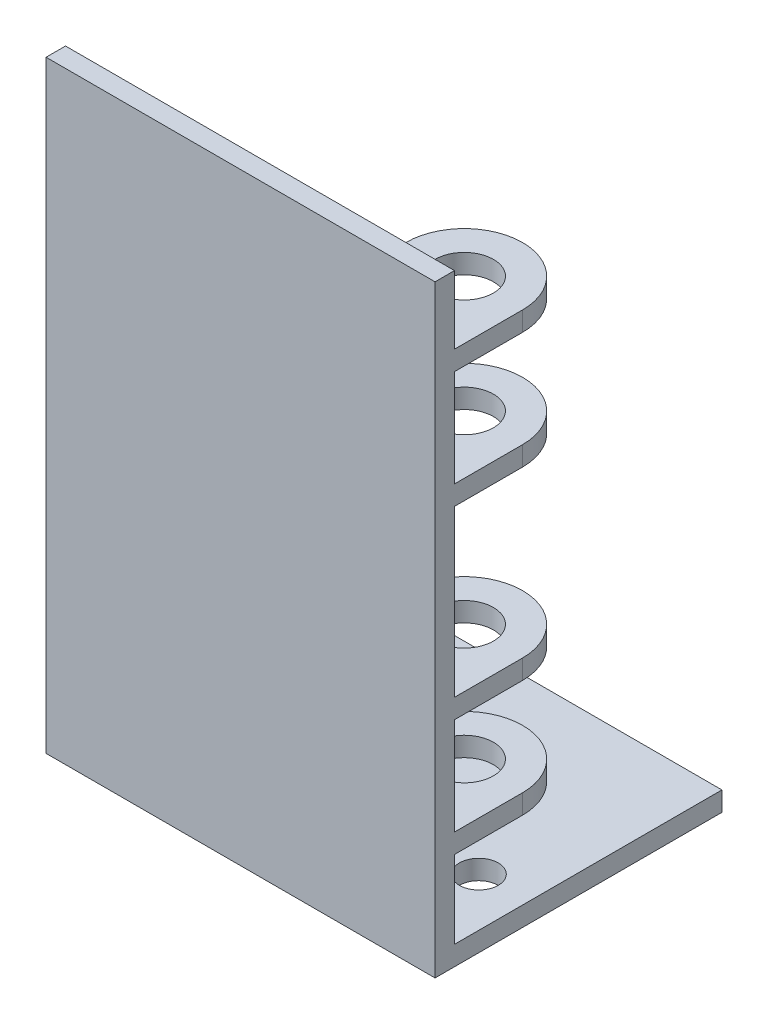
SolidWorks part; units mm, degrees
material "AISI 1045 Acero estirado en frío"
ref_plane "Front" through (0, 0, 0) normal (0, 0, 1) x (1, 0, 0)
ref_plane "Top" through (0, 0, 0) normal (0, 1, 0) x (1, 0, 0)
ref_plane "Right" through (0, 0, 0) normal (1, 0, 0) x (0, 0, -1)
sketch "Croquis2" plane through (0, 0, 0) normal (0, 1, 0) x (1, 0, 0)
  line L1 (20, 55) -> (20, 0) construction
  line L2 (0, 0) -> (40, 0)
  line L3 (0, 0) -> (0, 55)
  line L4 (0, 55) -> (40, 55)
  line L5 (40, 0) -> (40, 55)
  circle A0 centre (5, 47.5) radius 2
  circle A1 centre (35, 47.5) radius 2
  circle A2 centre (35, 7.5) radius 2
  circle A3 centre (5, 7.5) radius 2
  dimension "D2" = 30
  dimension "D3" = 4
  dimension "D4" = 7.5
  dimension "D5" = 5
  dimension "D6" = 7.5
  dimension "D7" = 40
  dimension "D1" = 5
  dimension "5.5" = 55
extrude "Saliente-Extruir1" add sketch "Croquis2" along normal blind 2
sketch "Croquis3" plane through (0, 0, 0) normal (0, 1, 0) x (1, 0, 0)
  line L0 (40, 0) -> (40, 55) construction
  line L1 (0, 0) -> (40, 0)
  line L2 (0, 0) -> (0, -2)
  line L3 (0, -2) -> (40, -2)
  line L4 (40, 0) -> (40, -2)
  dimension "D1" = 2
extrude "Saliente-Extruir2" add sketch "Croquis3" along normal blind 42
ref_plane "Plano1" through (0, 22, 0) normal (0, 1, 0) x (1, 0, 0)
sketch "Croquis4" plane through (0, 22, 0) normal (0, 1, 0) x (1, 0, 0)
  line L1 (40, 7) -> (40, 0)
  line L2 (0, 0) -> (40, 0) construction
  line L3 (40, 0) -> (28, 0)
  line L4 (40, 0) -> (0, 0) construction
  line L5 (28, 0) -> (28, 7)
  circle A0 centre (34, 7) radius 3
  arc A1 (40, 7) -> (28, 7) centre (34, 7) ccw
  dimension ".8" = 6
  dimension "1.9" = 6
  dimension "D2" = 7
extrude "Saliente-Extruir3" add sketch "Croquis4" along normal blind 2
pattern_linear "MatrizL1" count 2 spacing 12 along (0, -1, 0) of "Saliente-Extruir3"
sketch "Croquis5" plane through (0, 0, 0) normal (0, 0, -1) x (-1, 0, 0)
  line L0 (-40, 22) -> (-40, 12) construction
  line L1 (-28, 12) -> (-40, 12)
  line L2 (-28, 12) -> (-28, 22)
  line L3 (-28, 22) -> (-40, 22)
  line L4 (-40, 12) -> (-40, 22)
  line L5 (-28, 22) -> (-40, 22) construction
extrude "Saliente-Extruir4" [suppressed] add sketch "Croquis5" along normal blind 2
sketch "Croquis6" plane through (0, 2, 0) normal (0, 1, 0) x (1, 0, 0)
  line L0 (0, 27.5) -> (40, 27.5)
  line L1 (0, 55) -> (0, 0) construction
  line L2 (40, 0) -> (40, 55) construction
  line L4 (40, 55) -> (0, 55) construction
  line L9 (0, 55) -> (0, 0)
  line L10 (0, 0) -> (40, 0)
  line L11 (40, 0) -> (40, 55)
  line L12 (40, 55) -> (0, 55)
  line L13 (0, 55) -> (0, 27.5)
  line L15 (40, 27.5) -> (40, 55)
  line L16 (40, 55) -> (0, 55)
  dimension "D1" = 27.5
  dimension "D2" = 0
extrude "Cortar-Extruir1" cut sketch "Croquis6" against normal through all
sketch "Croquis7" plane through (0, 42, 0) normal (0, 1, 0) x (1, 0, 0)
  line L4 (0, 0) -> (0, -2)
  line L5 (0, -2) -> (40, -2)
  line L6 (40, -2) -> (40, 0)
  line L7 (40, 0) -> (0, 0)
  line L8 (0, 0) -> (0, -2)
  line L9 (0, -2) -> (40, -2)
  line L10 (40, -2) -> (40, 0)
  line L11 (40, 0) -> (0, 0)
  dimension "D1" = 0
extrude "Saliente-Extruir5" add sketch "Croquis7" along normal blind 20
pattern_linear "MatrizL2" count 2 spacing 31 along (0, 1, 0) of "MatrizL1", "Saliente-Extruir4"
